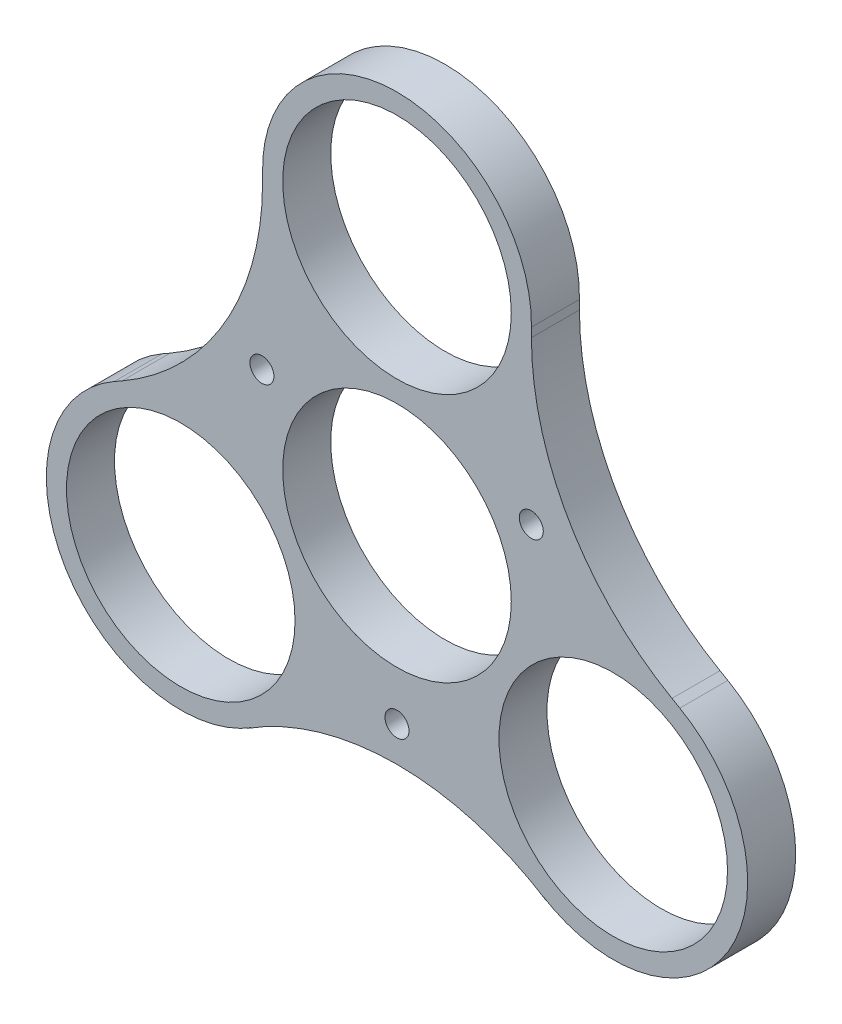
SolidWorks part; units mm, degrees
ref_plane "Front Plane" through (0, 0, 0) normal (0, 0, 1) x (1, 0, 0)
ref_plane "Top Plane" through (0, 0, 0) normal (0, 1, 0) x (1, 0, 0)
ref_plane "Right Plane" through (0, 0, 0) normal (1, 0, 0) x (0, 0, -1)
sketch "Sketch1" plane through (0, 0, 0) normal (0, 0, 1) x (1, 0, 0)
  line L0 (0, 39.8428) -> (0, -44.5449) construction
  line L1 (0, 0) -> (56.2144, -32.4554) construction
  line L2 (0, 0) -> (-52.6162, -30.378) construction
  line L3 (13.9984, 25.7887) -> (13.9976, 24.845)
  line L4 (28.632, -0.371) -> (29.4518, -0.8384)
  line L5 (-13.9993, 24.7065) -> (-13.9956, 25.6502)
  line L6 (-28.6325, -0.3712) -> (-29.4523, -0.8387)
  line L7 (15.5856, -25.1842) -> (14.9926, -24.8063)
  line L8 (-15.5856, -25.1842) -> (-14.9926, -24.8063)
  circle A0 centre (0, 0) radius 11.9
  circle A1 centre (0, 26) radius 11.9
  circle A2 centre (22.5167, -13) radius 11.9
  circle A3 centre (-22.5167, -13) radius 11.9
  arc A5 (14.9926, -24.8063) -> (29.4518, -0.8384) centre (22.5167, -13) ccw
  arc A6 (-29.4523, -0.8387) -> (-14.9926, -24.8063) centre (-22.5167, -13) ccw
  arc A8 (-15.5856, -25.1842) -> (15.5856, -25.1842) centre (0, -49.6401) cw
  arc A9 (-28.6325, -0.3712) -> (-13.9993, 24.7065) centre (-42.9991, 24.8201) ccw
  arc A10 (28.632, -0.371) -> (13.9976, 24.845) centre (42.9976, 24.8209) cw
  circle A11 centre (13.9836, 7.9823) radius 1.25
  circle A12 centre (0, -17) radius 1.25
  circle A13 centre (-14.065, 7.9367) radius 1.25
  arc A14 (13.9984, 25.7887) -> (-13.9956, 25.6502) centre (0, 26) ccw
  point P29 (0, -15.2516)
  point P32 (-14.065, 7.9367)
  point P35 (13.9836, 7.9823)
  dimension "D1" = 23.8
  dimension "D4" = 26
  dimension "D7" = 14
  dimension "D8" = 28
  dimension "D9" = 28
  dimension "D11" = 29
  dimension "D12" = 2.5
  dimension "D13" = 2.5
  dimension "D14" = 2.5
  dimension "D2" = 60
  dimension "D3" = 60
  dimension "D5" = 26
  dimension "D6" = 26
extrude "Boss-Extrude1" add sketch "Sketch1" along normal mid plane 5
